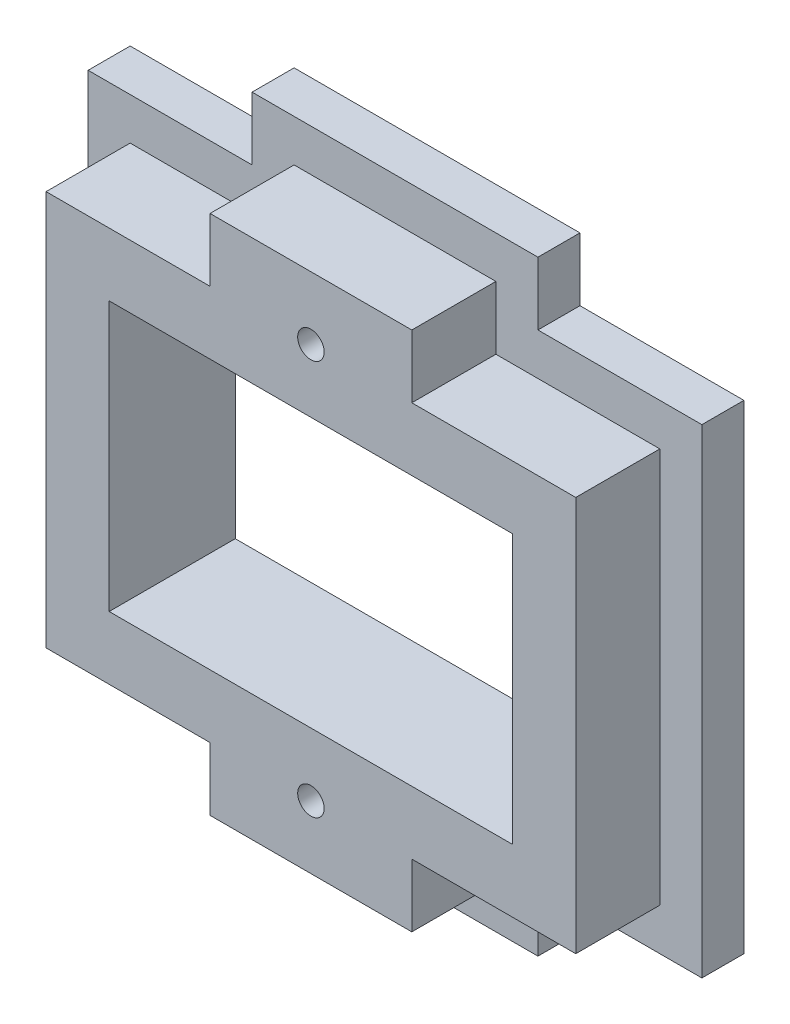
SolidWorks part; units mm, degrees
ref_plane "Front Plane" through (0, 0, 0) normal (0, 0, 1) x (1, 0, 0)
ref_plane "Top Plane" through (0, 0, 0) normal (0, 1, 0) x (1, 0, 0)
ref_plane "Right Plane" through (0, 0, 0) normal (1, 0, 0) x (0, 0, -1)
sketch "Sketch1" plane through (0, 0, 0) normal (0, 0, 1) x (1, 0, 0)
  line L0 (0, 0) -> (0, 9.8425) construction
  line L1 (7.62, -5.08) -> (-7.62, -5.08)
  line L2 (7.62, -5.08) -> (7.62, 5.08)
  line L3 (7.62, 5.08) -> (-7.62, 5.08)
  line L4 (-7.62, -5.08) -> (-7.62, 5.08)
  line L5 (7.62, -5.08) -> (-7.62, 5.08) construction
  line L6 (7.62, 5.08) -> (-7.62, -5.08) construction
  line L7 (10.0012, -7.4613) -> (-10.0012, -7.4613)
  line L8 (10.0012, -7.4613) -> (10.0012, 7.4612)
  line L9 (10.0012, 7.4612) -> (-10.0012, 7.4612)
  line L10 (-10.0012, -7.4613) -> (-10.0012, 7.4612)
  line L11 (10.0012, -7.4613) -> (-10.0012, 7.4612) construction
  line L12 (10.0012, 7.4612) -> (-10.0012, -7.4613) construction
  line L13 (-3.81, 7.4612) -> (3.81, 7.4612)
  line L14 (-3.81, 7.4612) -> (-3.81, 9.8425)
  line L15 (-3.81, 9.8425) -> (3.81, 9.8425)
  line L16 (3.81, 7.4612) -> (3.81, 9.8425)
  line L17 (0, 0) -> (10.0012, 0) construction
  line L18 (3.81, -7.4613) -> (3.81, -9.8425)
  line L19 (-3.81, -9.8425) -> (3.81, -9.8425)
  line L20 (-3.81, -7.4613) -> (-3.81, -9.8425)
  line L21 (-3.81, -7.4613) -> (3.81, -7.4613)
  circle A0 centre (0, 7.4612) radius 0.5
  circle A1 centre (0, -7.4613) radius 0.5
  point P0 (0, 0)
  point P6 (0, 0)
  point P17 (0, 9.8425)
  dimension "D5" = 1
  dimension "D1" = 10.16
  dimension "D2" = 15.24
  dimension "D3" = 2.3813
  dimension "D4" = 7.62
  dimension "D6" = 2.3813
  dimension "D7" = 2.3813
extrude "Boss-Extrude1" add sketch "Sketch1" along normal blind 3.175 contours L7 A1 L8 L9 A0 L10 L1 L4 L3 L2 | A0 L9 L16 L15 L14 | L7 A1 L20 L19 L18
sketch "Sketch2" plane through (0, 0, 0) normal (0, 0, -1) x (-1, 0, 0)
  line L13 (-7.62, 5.08) -> (7.62, 5.08)
  line L14 (-7.62, 5.08) -> (-7.62, -5.08)
  line L15 (-7.62, -5.08) -> (7.62, -5.08)
  line L16 (7.62, 5.08) -> (7.62, -5.08)
  line L24 (5.3975, -9.0488) -> (11.5887, -9.0488)
  line L25 (11.5887, -9.0488) -> (11.5887, 9.0487)
  line L26 (11.5887, 9.0487) -> (5.3975, 9.0487)
  line L27 (5.3975, 9.0487) -> (5.3975, 11.43)
  line L28 (5.3975, 11.43) -> (-5.3975, 11.43)
  line L29 (-5.3975, 11.43) -> (-5.3975, 9.0487)
  line L30 (-5.3975, 9.0487) -> (-11.5887, 9.0488)
  line L31 (-11.5887, 9.0488) -> (-11.5887, -9.0488)
  line L32 (-11.5887, -9.0488) -> (-5.3975, -9.0488)
  line L33 (-5.3975, -9.0488) -> (-5.3975, -11.43)
  line L34 (-5.3975, -11.43) -> (5.3975, -11.43)
  line L35 (5.3975, -11.43) -> (5.3975, -9.0488)
  line L36 (5.3975, -9.0488) -> (11.5887, -9.0488)
  line L37 (11.5887, -9.0488) -> (11.5887, 9.0487)
  line L38 (11.5887, 9.0487) -> (5.3975, 9.0487)
  line L39 (5.3975, 9.0487) -> (5.3975, 11.43)
  line L40 (5.3975, 11.43) -> (-5.3975, 11.43)
  line L41 (-5.3975, 11.43) -> (-5.3975, 9.0487)
  line L42 (-5.3975, 9.0487) -> (-11.5887, 9.0488)
  line L43 (-11.5887, 9.0488) -> (-11.5887, -9.0488)
  line L44 (-11.5887, -9.0488) -> (-5.3975, -9.0488)
  line L45 (-5.3975, -9.0488) -> (-5.3975, -11.43)
  line L46 (-5.3975, -11.43) -> (5.3975, -11.43)
  line L47 (5.3975, -11.43) -> (5.3975, -9.0488)
  dimension "D1" = 1.5875
extrude "Boss-Extrude2" add sketch "Sketch2" along normal blind 1.5875
